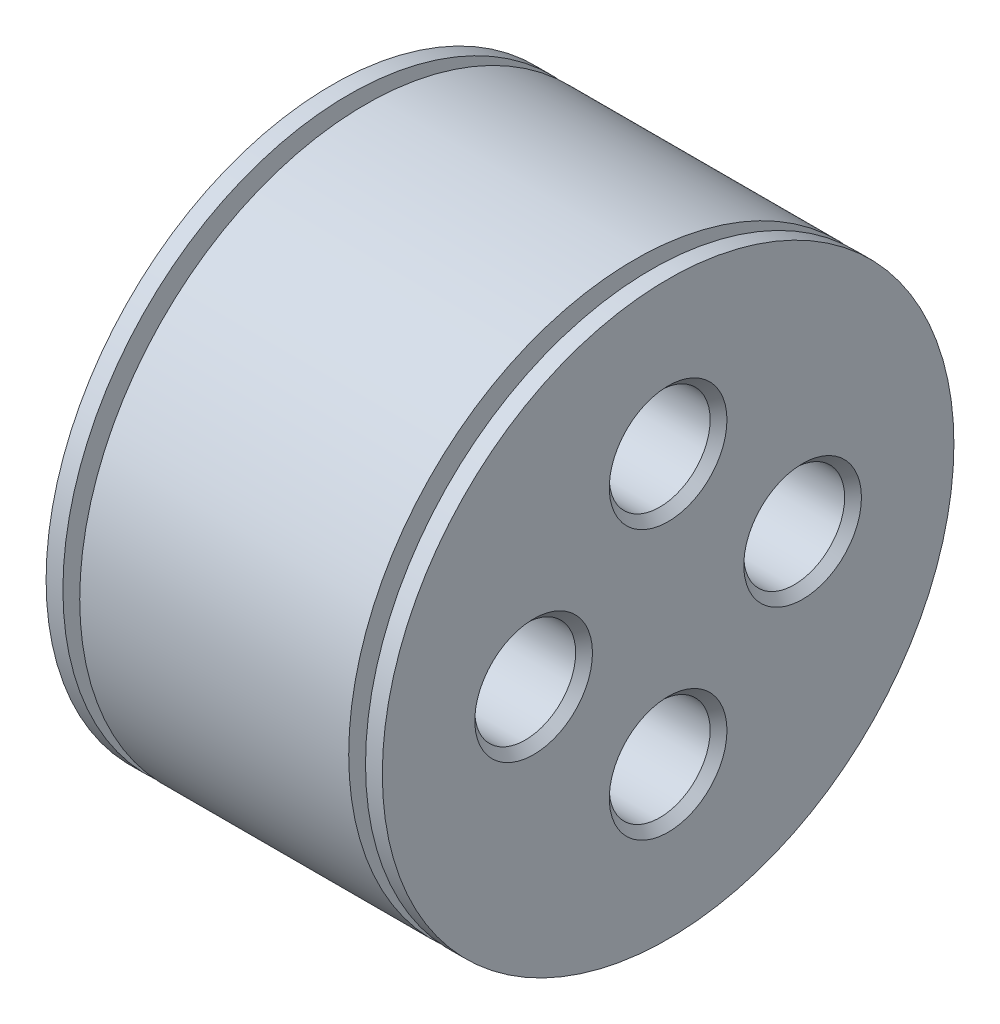
SolidWorks part; units mm, degrees
ref_plane "Front Plane" through (0, 0, 0) normal (0, 0, 1) x (1, 0, 0)
ref_plane "Top Plane" through (0, 0, 0) normal (0, 1, 0) x (1, 0, 0)
ref_plane "Right Plane" through (0, 0, 0) normal (1, 0, 0) x (0, 0, -1)
sketch "Sketch1" plane through (0, 0, 0) normal (1, 0, 0) x (0, 0, -1)
  circle A0 centre (0, 0) radius 17
  dimension "D1" = 34
extrude "Boss-Extrude1" add sketch "Sketch1" along normal blind 1
sketch "Sketch2" plane through (1, 0, 0) normal (1, 0, 0) x (0, 0, -1)
  circle A0 centre (0, 0) radius 15
  circle A1 centre (0, 0) radius 17 construction
  dimension "D1" = 2
extrude "Boss-Extrude2" add sketch "Sketch2" along normal blind 1
sketch "Sketch4" plane through (2, 0, 0) normal (1, 0, 0) x (0, 0, -1)
  circle A0 centre (0, 0) radius 17
  dimension "D1" = 34
extrude "Boss-Extrude3" add sketch "Sketch4" along normal blind 16
sketch "Sketch5" plane through (18, 0, 0) normal (1, 0, 0) x (0, 0, -1)
  circle A0 centre (0, 0) radius 13
  dimension "D1" = 26
extrude "Boss-Extrude4" add sketch "Sketch5" along normal blind 1
sketch "Sketch6" plane through (19, 0, 0) normal (1, 0, 0) x (0, 0, -1)
  circle A0 centre (0, 0) radius 17
  dimension "D1" = 34
extrude "Boss-Extrude5" add sketch "Sketch6" along normal blind 1
sketch "Sketch7" plane through (0, 0, 0) normal (-1, 0, 0) x (0, 0, 1)
  circle A0 centre (0, 0) radius 11
  dimension "D1" = 22
extrude "Cut-Extrude1" cut sketch "Sketch7" against normal blind 6
sketch "Sketch8" plane through (6, 0, 0) normal (-1, 0, 0) x (0, 0, 1)
  circle A0 centre (0, 8) radius 1.5
  circle A1 centre (8, 0) radius 1.5
  circle A2 centre (0, -8) radius 1.5
  circle A3 centre (-8, 0) radius 1.5
  point P8 (0, 0)
  point P11 (-3.7865, 6.4819)
  point P12 (2.4173, -1.9039)
  point P14 (-1.2622, -0.4065)
  dimension "D1" = 3
  dimension "D2" = 16
  dimension "D3" = 8
  dimension "D4" = 16
  dimension "D5" = 8
extrude "Cut-Extrude2" cut sketch "Sketch8" against normal blind 14
sketch "Sketch9" plane through (20, 0, 0) normal (1, 0, 0) x (0, 0, -1)
  circle A0 centre (-8, 0) radius 3
  circle A1 centre (0, 8) radius 3
  circle A3 centre (8, 0) radius 3
  circle A4 centre (0, -8) radius 3
  dimension "D1" = 6
extrude "Cut-Extrude3" cut sketch "Sketch9" against normal blind 5
chamfer "Chamfer1" distance 0.5 angle 45 4 edges at (20, 8, -3) (20, 0, 5) (20, 0, -11) (20, -8, -3)
